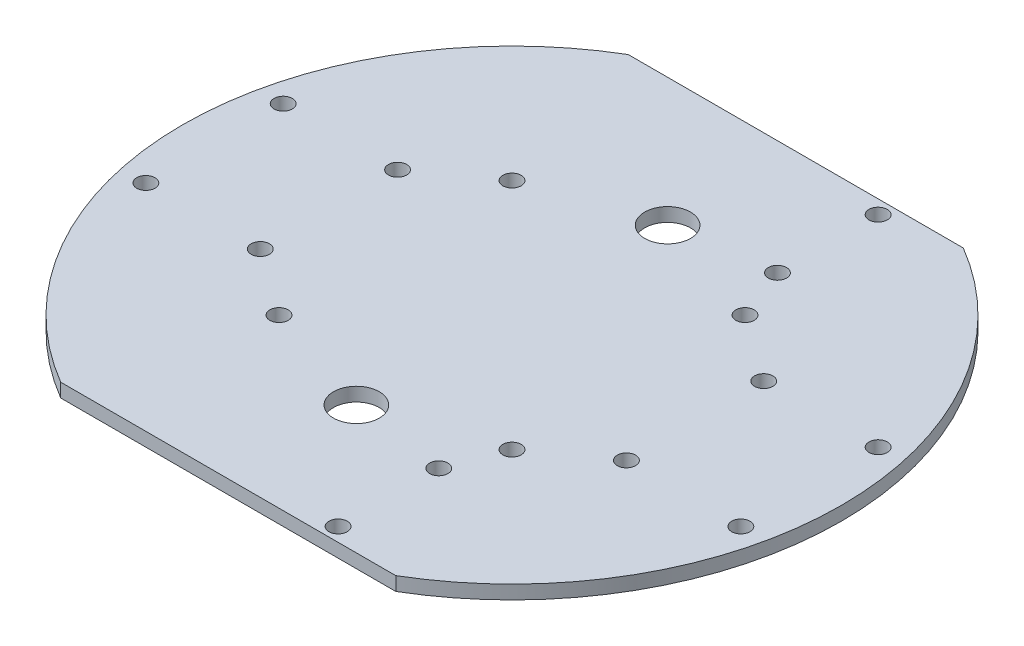
SolidWorks part; units mm, degrees
ref_plane "Front Plane" through (0, 0, 0) normal (0, 0, 1) x (1, 0, 0)
ref_plane "Top Plane" through (0, 0, 0) normal (0, 1, 0) x (1, 0, 0)
ref_plane "Right Plane" through (0, 0, 0) normal (1, 0, 0) x (0, 0, -1)
sketch "Sketch1" plane through (0, 0, 0) normal (0, 1, 0) x (1, 0, 0)
  line L0 (0, 72) -> (0, -72) construction
  line L1 (-72, 0) -> (72, 0) construction
  line L2 (0, -72) -> (0, -62)
  line L3 (-36.606, -62) -> (36.606, -62)
  line L4 (0, 0) -> (50.9117, -50.9117) construction
  line L5 (50.9117, -50.9117) -> (-50.9117, 50.9117) construction
  line L6 (0, 0) -> (50.9117, 50.9117) construction
  line L7 (50.9117, 50.9117) -> (-50.9117, -50.9117) construction
  line L8 (0, -62) -> (21, -62)
  line L9 (21, -62) -> (21, 62)
  line L10 (-36.606, 62) -> (36.606, 62)
  circle A0 centre (0, 0) radius 72
  circle A1 centre (-65, 15) radius 2
  circle A2 centre (-40, 15) radius 2
  circle A3 centre (-40, -15) radius 2
  circle A4 centre (-65, -15) radius 2
  circle A5 centre (40, -15) radius 2
  circle A6 centre (65, -15) radius 2
  circle A7 centre (65, 15) radius 2
  circle A8 centre (40, 15) radius 2
  circle A13 centre (25.4558, 25.4558) radius 2
  circle A14 centre (25.4558, -25.4558) radius 2
  circle A15 centre (-25.4558, -25.4558) radius 2
  circle A16 centre (-25.4558, 25.4558) radius 2
  circle A17 centre (21, -59) radius 2
  circle A18 centre (21, -37) radius 2
  circle A19 centre (21, 59) radius 2
  circle A20 centre (21, 37) radius 2
  circle A21 centre (0, -34) radius 5
  circle A22 centre (0, 34) radius 5
  point P34 (0, 0)
  point P35 (0, -62)
  point P43 (0, 0)
  point P54 (21, 0)
  dimension "D1" = 4
  dimension "D2" = 25
  dimension "D5" = 3
  dimension "D7" = 10
  dimension "D8" = 4
  dimension "D6" = 22
  dimension "D10" = 23
  dimension "D11" = 10
  dimension "D3" = 15
  dimension "D4" = 40
  dimension "D9" = 36
extrude "Boss-Extrude2" add sketch "Sketch1" along normal blind 3 contours L9 A20 A19 L10 A0 L3 A17 A18 A4 A1 A2 A3 A15 A16 A21 A22 | L9 A20 A18 A17 L3 A0 L10 A19 A14 A13 A7 A6 A5 A8
